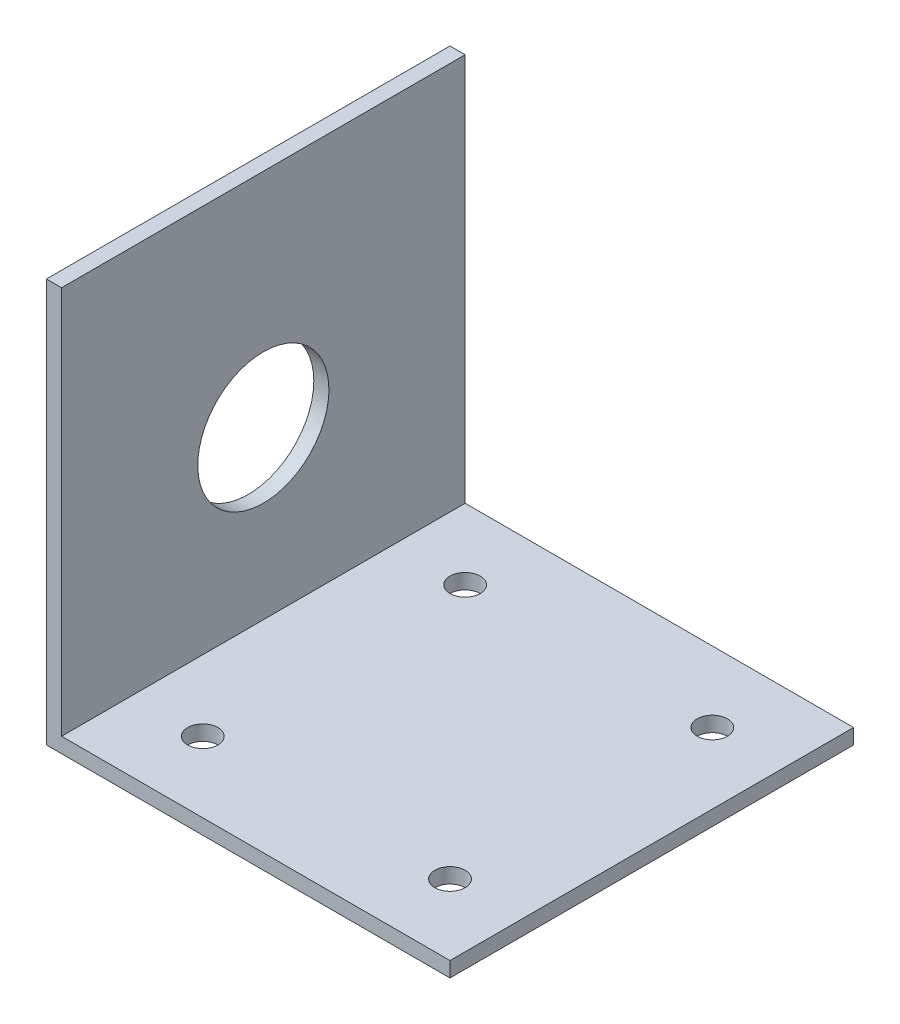
SolidWorks part; units mm, degrees
ref_plane "Plan de face" through (0, 0, 0) normal (0, 0, 1) x (1, 0, 0)
ref_plane "Plan de dessus" through (0, 0, 0) normal (0, 1, 0) x (1, 0, 0)
ref_plane "Plan de droite" through (0, 0, 0) normal (1, 0, 0) x (0, 0, -1)
sketch "Esquisse1" plane through (0, 0, 0) normal (0, 0, 1) x (1, 0, 0)
  line L0 (0, 0) -> (0, 40)
  line L1 (0, 40) -> (1.5, 40)
  line L2 (1.5, 40) -> (1.5, 1.5)
  line L3 (1.5, 1.5) -> (40, 1.5)
  line L4 (40, 1.5) -> (40, 0)
  line L5 (40, 0) -> (0, 0)
  dimension "D1" = 40
  dimension "D2" = 40
  dimension "D3" = 1.5
  dimension "D4" = 1.5
extrude "Extrusion1" add sketch "Esquisse1" along normal blind 40
sketch "Esquisse2" plane through (1.5, 0, 0) normal (1, 0, 0) x (0, 0, -1)
  line L0 (-40, 0) -> (0, 0) construction
  line L1 (0, 1.5) -> (0, 40) construction
  circle A0 centre (-20, 18) radius 6.5
  dimension "D1" = 13
  dimension "D2" = 18
  dimension "D3" = 20
extrude "Extrusion2" cut sketch "Esquisse2" against normal blind 30
sketch "Esquisse3" plane through (0, 1.5, 0) normal (0, 1, 0) x (-1, 0, 0)
  line L0 (-40, 40) -> (-1.5, 40) construction
  line L1 (-40, 0) -> (-1.5, 0) construction
  line L2 (-1.5, 40) -> (-1.5, 0) construction
  line L3 (-40, 40) -> (-40, 0) construction
  circle A0 centre (-8.5, 33) radius 1.5
  circle A1 centre (-8.5, 7) radius 1.5
  circle A2 centre (-33, 7) radius 1.5
  circle A3 centre (-33, 33) radius 1.5
  dimension "D1" = 7
  dimension "D2" = 7
  dimension "D3" = 7
  dimension "D4" = 7
  dimension "D6" = 7
  dimension "D7" = 7
  dimension "D8" = 7
  dimension "D9" = 7
extrude "Extrusion3" cut sketch "Esquisse3" against normal blind 30
